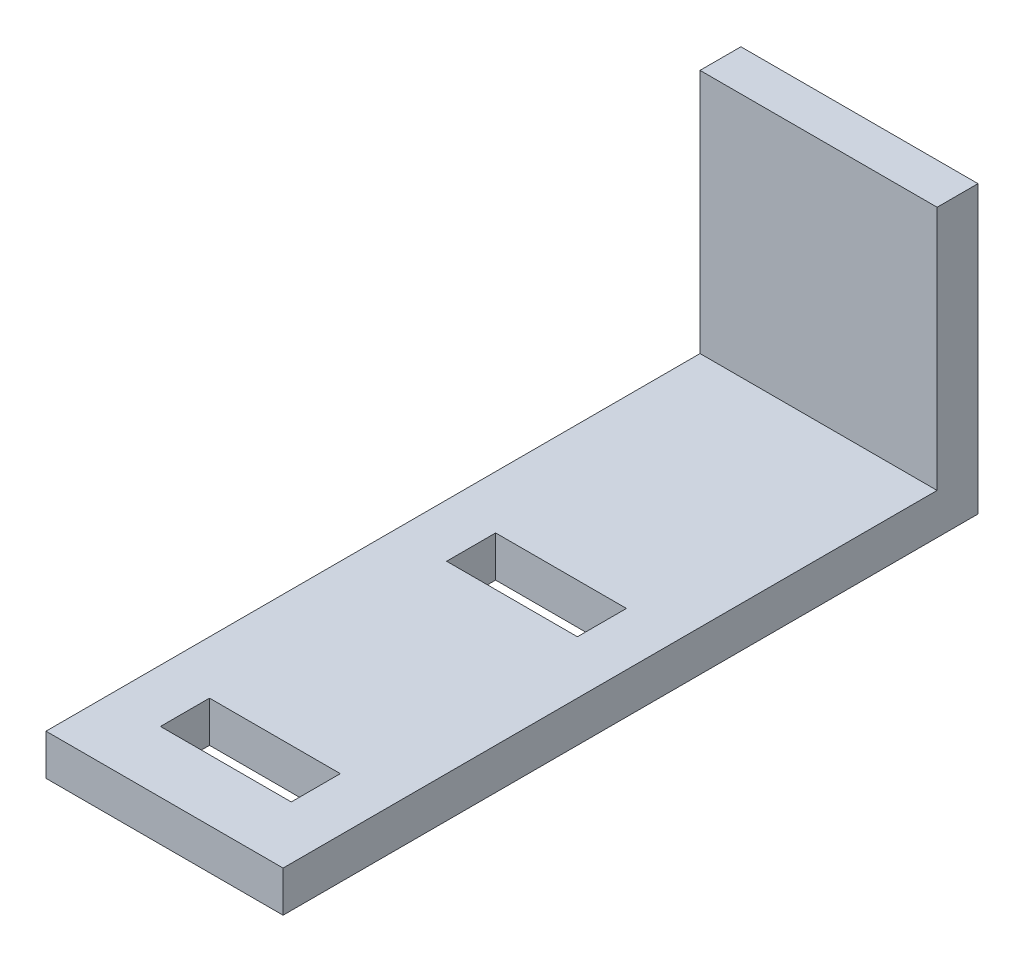
SolidWorks part; units mm, degrees
ref_plane "Piano frontale" through (0, 0, 0) normal (0, 0, 1) x (1, 0, 0)
ref_plane "Piano superiore" through (0, 0, 0) normal (0, 1, 0) x (1, 0, 0)
ref_plane "Piano destro" through (0, 0, 0) normal (1, 0, 0) x (0, 0, -1)
sketch "Schizzo1" plane through (0, 0, 0) normal (0, 0, 1) x (1, 0, 0)
  line L1 (-14.5, 17.5) -> (14.5, 17.5)
  line L2 (-14.5, 17.5) -> (-14.5, -17.5)
  line L3 (-14.5, -17.5) -> (14.5, -17.5)
  line L4 (14.5, 17.5) -> (14.5, -17.5)
  dimension "D1" = 35
  dimension "D2" = 29
extrude "Estrusione-Estrusione1" add sketch "Schizzo1" along normal blind 5
sketch "Schizzo2" plane through (0, 0, 5) normal (0, 0, 1) x (1, 0, 0)
  line L0 (14.5, -17.5) -> (14.5, 17.5) construction
  line L1 (-14.5, -17.5) -> (14.5, -17.5)
  line L2 (-14.5, -17.5) -> (-14.5, -12.5)
  line L3 (-14.5, -12.5) -> (14.5, -12.5)
  line L4 (14.5, -17.5) -> (14.5, -12.5)
  dimension "D1" = 5
extrude "Estrusione-Estrusione2" add sketch "Schizzo2" along normal blind 80
sketch "Schizzo4" plane through (0, -12.5, 0) normal (0, 1, 0) x (1, 0, 0)
  line L0 (0, 5.4511) -> (0, -74.8079) construction
  line L1 (-8, -36.5) -> (8, -36.5)
  line L2 (-8, -36.5) -> (-8, -42.5)
  line L3 (-8, -42.5) -> (8, -42.5)
  line L4 (8, -36.5) -> (8, -42.5)
  line L8 (-8, -71.5) -> (-8, -77.5)
  line L9 (-8, -77.5) -> (8, -77.5)
  line L10 (-8, -71.5) -> (8, -71.5)
  line L11 (8, -71.5) -> (8, -77.5)
  line L13 (14.5, -85) -> (-14.5, -85) construction
  dimension "D1" = 16
  dimension "D2" = 6
  dimension "D3" = 7.5
  dimension "D4" = 2
  dimension "D5" = 29
extrude "Taglio-Estrusione2" cut sketch "Schizzo4" against normal blind 10
